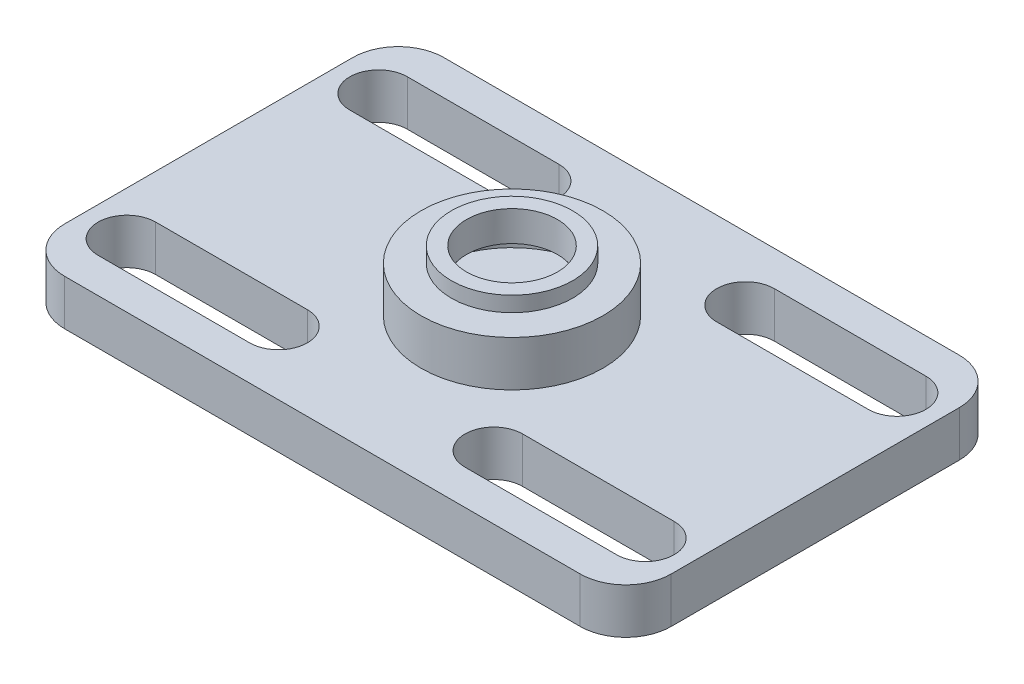
SolidWorks part; units mm, degrees
material "Cast Alloy Steel"
ref_plane "Front Plane" through (0, 0, 0) normal (0, 0, 1) x (1, 0, 0)
ref_plane "Top Plane" through (0, 0, 0) normal (0, 1, 0) x (1, 0, 0)
ref_plane "Right Plane" through (0, 0, 0) normal (1, 0, 0) x (0, 0, -1)
sketch "Sketch1" plane through (0, 0, 0) normal (0, 1, 0) x (1, 0, 0)
  circle A0 centre (0, 0) radius 15
  circle A1 centre (0, 0) radius 20
  dimension "D1" = 30
  dimension "D2" = 40
extrude "Boss-Extrude1" add sketch "Sketch1" against normal blind 5
sketch "Sketch2" plane through (0, -5, 0) normal (0, -1, 0) x (1, 0, 0)
  circle A0 centre (0, 0) radius 15
  circle A1 centre (0, 0) radius 30
  dimension "D1" = 60
extrude "Boss-Extrude2" add sketch "Sketch2" along normal blind 15
sketch "Sketch3" plane through (0, -20, 0) normal (0, -1, 0) x (1, 0, 0)
  circle A0 centre (0, 0) radius 27.5
  dimension "D1" = 55
extrude "Cut-Extrude1" cut sketch "Sketch3" against normal offset from surface (10 mm away) 5 up to face at (0, -5, 20)
sketch "Sketch4" plane through (0, -20, 0) normal (0, -1, 0) x (1, 0, 0)
  line L0 (-100, 62.5) -> (-100, -62.5)
  line L1 (-100, 62.5) -> (100, 62.5)
  line L2 (-100, -62.5) -> (100, -62.5)
  line L3 (100, 62.5) -> (100, -62.5)
  line L4 (-100, 62.5) -> (100, -62.5) construction
  line L5 (-100, -62.5) -> (100, 62.5) construction
  line L6 (-85.5, 41.5) -> (-35.5, 41.5) construction
  line L7 (-85.5, 51) -> (-35.5, 51)
  line L8 (-85.5, 32) -> (-35.5, 32)
  line L9 (-1000, 0) -> (49000, 0) construction
  line L10 (0, -1000) -> (0, 49000) construction
  line L11 (-85.5, -41.5) -> (-35.5, -41.5) construction
  line L12 (-85.5, -51) -> (-35.5, -51)
  line L13 (-85.5, -32) -> (-35.5, -32)
  line L14 (85.5, 41.5) -> (35.5, 41.5) construction
  line L15 (85.5, 51) -> (35.5, 51)
  line L16 (85.5, 32) -> (35.5, 32)
  line L17 (85.5, -41.5) -> (35.5, -41.5) construction
  line L18 (85.5, -51) -> (35.5, -51)
  line L19 (85.5, -32) -> (35.5, -32)
  arc A0 (-85.5, 51) -> (-85.5, 32) centre (-85.5, 41.5) ccw
  arc A1 (-35.5, 32) -> (-35.5, 51) centre (-35.5, 41.5) ccw
  arc A2 (-85.5, -51) -> (-85.5, -32) centre (-85.5, -41.5) cw
  arc A3 (-35.5, -32) -> (-35.5, -51) centre (-35.5, -41.5) cw
  arc A4 (85.5, 51) -> (85.5, 32) centre (85.5, 41.5) cw
  arc A5 (35.5, 32) -> (35.5, 51) centre (35.5, 41.5) cw
  arc A6 (85.5, -51) -> (85.5, -32) centre (85.5, -41.5) ccw
  arc A7 (35.5, -32) -> (35.5, -51) centre (35.5, -41.5) ccw
  point P1 (0, 0)
  point P3 (-60.5, 41.5)
  point P19 (-60.5, -41.5)
  point P26 (60.5, 41.5)
  point P33 (60.5, -41.5)
  dimension "D6" = 9.5
  dimension "D1" = 200
  dimension "D2" = 125
  dimension "D3" = 50
  dimension "D4" = 11.5
  dimension "D5" = 14.5
extrude "Boss-Extrude3" add sketch "Sketch4" along normal blind 15
fillet "Fillet1" radius 15 4 edges at (100, -27.5, 62.5) (100, -27.5, -62.5) (-100, -27.5, 62.5) (-100, -27.5, -62.5)
